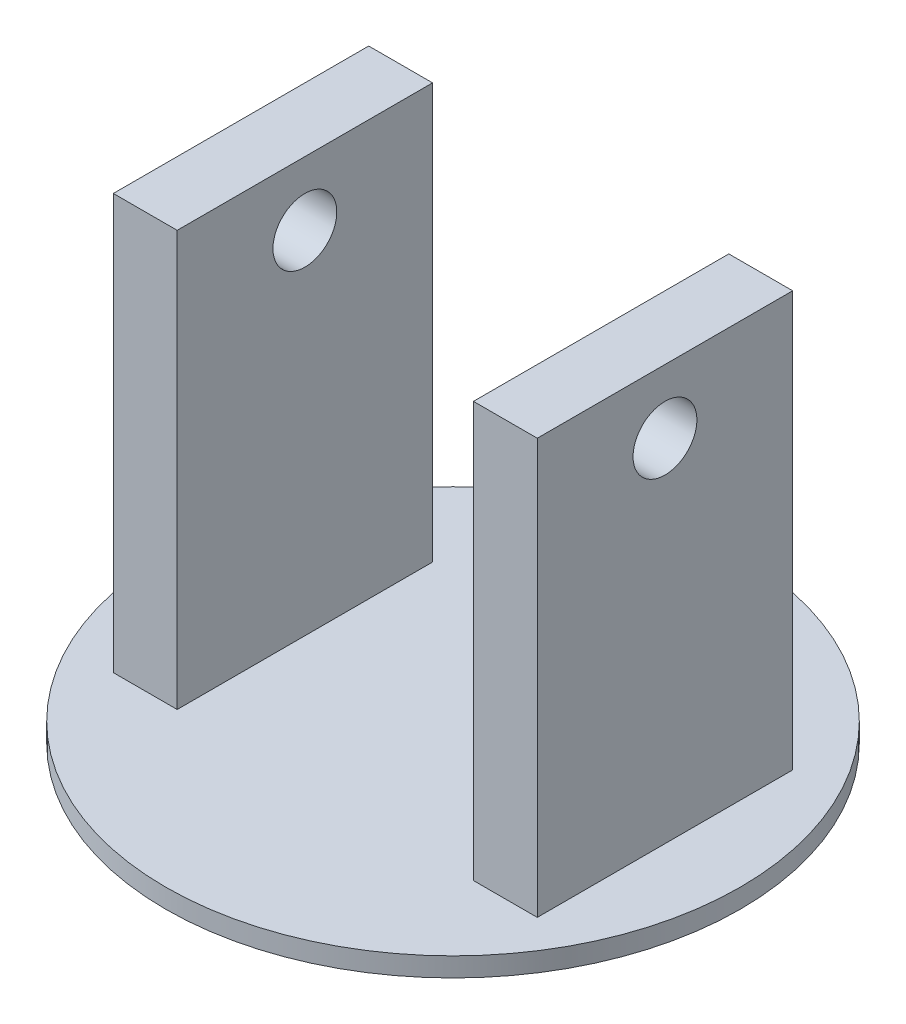
SolidWorks part; units mm, degrees
ref_plane "Front Plane" through (0, 0, 0) normal (0, 0, 1) x (1, 0, 0)
ref_plane "Top Plane" through (0, 0, 0) normal (0, 1, 0) x (1, 0, 0)
ref_plane "Right Plane" through (0, 0, 0) normal (1, 0, 0) x (0, 0, -1)
sketch "Sketch1" plane through (0, 0, 0) normal (0, 1, 0) x (1, 0, 0)
  circle A0 centre (0, 0) radius 45
  dimension "D1" = 90
extrude "Boss-Extrude1" add sketch "Sketch1" along normal blind 3
sketch "Sketch2" plane through (0, 3, 0) normal (0, 1, 0) x (1, 0, 0)
  line L0 (0, -31.5859) -> (0, 31.5859) construction
  line L1 (-33.2008, -20) -> (-23.2008, -20)
  line L2 (-33.2008, -20) -> (-33.2008, 20)
  line L3 (-33.2008, 20) -> (-23.2008, 20)
  line L4 (-23.2008, -20) -> (-23.2008, 20)
  line L5 (-33.2008, -20) -> (-23.2008, 20) construction
  line L6 (-33.2008, 20) -> (-23.2008, -20) construction
  line L7 (33.2008, 20) -> (23.2008, 20)
  line L8 (23.2008, -20) -> (23.2008, 20)
  line L9 (33.2008, -20) -> (23.2008, -20)
  line L10 (33.2008, -20) -> (33.2008, 20)
  circle A1 centre (0, 0) radius 45
  circle A2 centre (0, 0) radius 45
  point P0 (-28.2008, 0)
  point P11 (0, 0)
  dimension "D2" = 40
  dimension "D3" = 10
  dimension "D1" = 0
extrude "Boss-Extrude2" add sketch "Sketch2" along normal blind 65 contours L1 L4 L3 L2 | L9 L10 L7 L8
sketch "Sketch3" plane through (-33.2008, 0, 0) normal (-1, 0, 0) x (0, 0, 1)
  line L4 (-20, 3) -> (20, 3)
  line L5 (20, 3) -> (20, 68)
  line L6 (20, 68) -> (-20, 68)
  line L7 (-20, 68) -> (-20, 3)
  line L8 (-20, 3) -> (20, 3)
  line L9 (20, 3) -> (20, 68)
  line L10 (20, 68) -> (-20, 68)
  line L11 (-20, 68) -> (-20, 3)
  circle A0 centre (0, 58) radius 5
  point P6 (0, 0)
  point P7 (0, 3)
  point P8 (0, 57.0966)
  dimension "D3" = 10
  dimension "D2" = 55
  dimension "D1" = 0
extrude "Cut-Extrude1" cut sketch "Sketch3" against normal up to surface (66.4016 mm away) contours A0 up to face at (33.2008, 35.5, 0)
